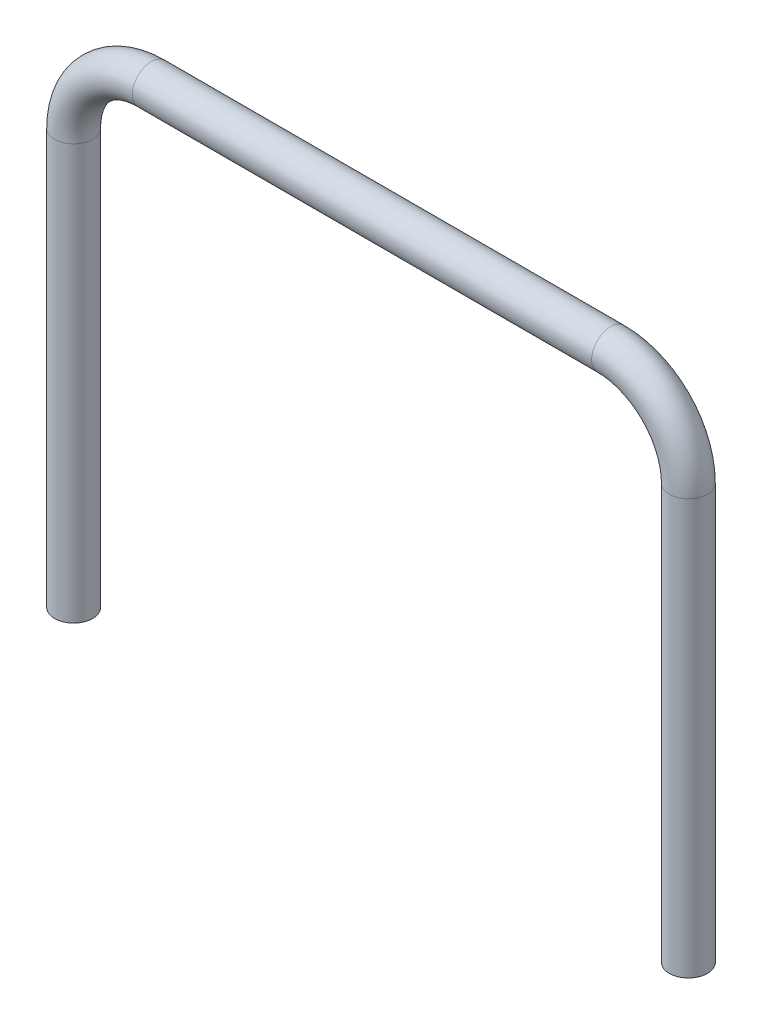
SolidWorks part; units mm, degrees
material "Brass"
ref_plane "Front Plane" through (0, 0, 0) normal (0, 0, 1) x (1, 0, 0)
ref_plane "Top Plane" through (0, 0, 0) normal (0, 1, 0) x (1, 0, 0)
ref_plane "Right Plane" through (0, 0, 0) normal (1, 0, 0) x (0, 0, -1)
sketch "Sketch1" plane through (0, 0, 0) normal (0, 0, 1) x (1, 0, 0)
  line L0 (-10.0457, -16.1036) -> (-10.0457, -2.54)
  line L1 (-7.5057, 0) -> (7.5057, 0)
  line L2 (10.0457, -2.54) -> (10.0457, -16.1036)
  arc A0 (-10.0457, -2.54) -> (-7.5057, 0) centre (-7.5057, -2.54) cw
  arc A1 (10.0457, -2.54) -> (7.5057, 0) centre (7.5057, -2.54) ccw
  point P2 (0, 0)
  point P8 (-10.0457, 0)
  point P11 (10.0457, 0)
  dimension "D3" = 2.54
  dimension "D4" = 2.54
  dimension "D1" = 20.0914
  dimension "D2" = 16.1036
ref_plane "Plane1" through (0, -16.1036, 0) normal (0, 1, 0) x (1, 0, 0)
sketch "Sketch2" plane through (0, -16.1036, 0) normal (0, 1, 0) x (1, 0, 0)
  circle A0 centre (-10.0457, 0) radius 0.6223
  dimension "D1" = 1.2446
sweep "Sweep1" add profiles "Sketch2" path "Sketch1"
